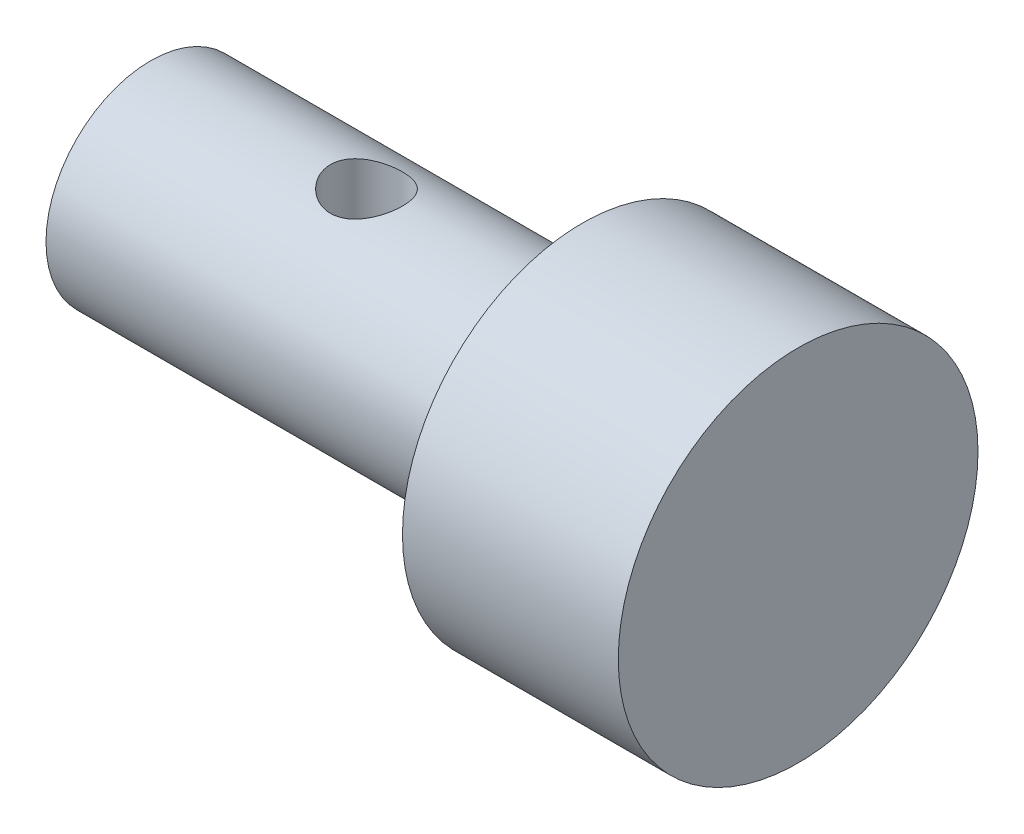
SolidWorks part; units mm, degrees
ref_plane "Front Plane" through (0, 0, 0) normal (0, 0, 1) x (1, 0, 0)
ref_plane "Top Plane" through (0, 0, 0) normal (0, 1, 0) x (1, 0, 0)
ref_plane "Right Plane" through (0, 0, 0) normal (1, 0, 0) x (0, 0, -1)
sketch "Sketch2" plane through (0, 0, 0) normal (1, 0, 0) x (0, 0, -1)
  circle A0 centre (0, 0) radius 1.455
  dimension "D1" = 2.91
extrude "Boss-Extrude3" add sketch "Sketch2" along normal blind 6 contours A0
sketch "Sketch3" plane through (6, 0, 0) normal (1, 0, 0) x (0, 0, -1)
  circle A0 centre (0, 0) radius 2.5
  dimension "D1" = 5
extrude "Boss-Extrude4" add sketch "Sketch3" along normal blind 3
sketch "Sketch4" plane through (0, 0, 0) normal (0, 1, 0) x (1, 0, 0)
  circle A0 centre (3, 0) radius 0.5
  dimension "D1" = 1
  dimension "D2" = 3
extrude "Cut-Extrude1" cut sketch "Sketch4" against normal through all both and the other way through all
